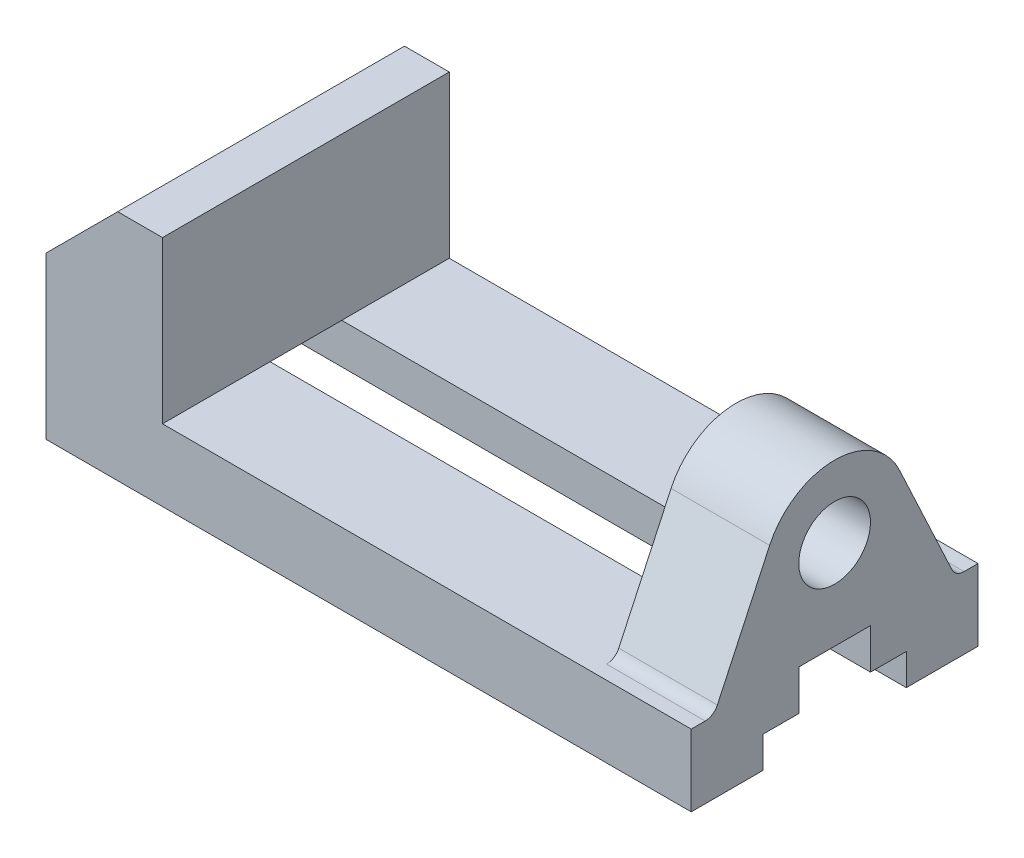
SolidWorks part; units mm, degrees
ref_plane "Front Plane" through (0, 0, 0) normal (0, 0, 1) x (1, 0, 0)
ref_plane "Top Plane" through (0, 0, 0) normal (0, 1, 0) x (1, 0, 0)
ref_plane "Right Plane" through (0, 0, 0) normal (1, 0, 0) x (0, 0, -1)
sketch "Sketch1" plane through (0, 0, 0) normal (0, 0, 1) x (1, 0, 0)
  line L1 (-72, 26) -> (72, 26)
  line L2 (-72, 26) -> (-72, -26)
  line L3 (-72, -26) -> (72, -26)
  line L4 (72, 26) -> (72, -26)
  line L5 (-72, 26) -> (72, -26) construction
  line L6 (-72, -26) -> (72, 26) construction
  point P0 (0, 0)
  dimension "D1" = 144
  dimension "D2" = 52
extrude "Boss-Extrude1" add sketch "Sketch1" along normal mid plane 64
sketch "Sketch2" plane through (0, 0, 32) normal (0, 0, 1) x (1, 0, 0)
  line L0 (-72, 26) -> (-72, -26) construction
  line L1 (-46, 40.9189) -> (50, 40.9189)
  line L2 (-46, 40.9189) -> (-46, -10)
  line L3 (-46, -10) -> (50, -10)
  line L4 (50, 40.9189) -> (50, -10)
  line L5 (72, 26) -> (-72, 26) construction
  line L6 (72, -26) -> (72, 26) construction
  dimension "D1" = 26
  dimension "D2" = 36
  dimension "D3" = 22
extrude "Cut-Extrude1" cut sketch "Sketch2" against normal blind 64
chamfer "Chamfer1" distance 16 distance2 16 1 edges at (-72, 26, 0)
sketch "Sketch3" plane through (72, 0, 0) normal (1, 0, 0) x (0, 0, -1)
  line L0 (-32, 26) -> (32, 26) construction
  line L1 (0, 10) -> (0, -29.5307) construction
  line L2 (28.8914, -10) -> (32, -10)
  line L3 (-28.8914, -10) -> (-32, -10)
  line L4 (-26.1725, -8.2679) -> (-14.5009, 16.7619)
  line L5 (14.5009, 16.7619) -> (26.1725, -8.2679)
  line L6 (-32, -26) -> (-32, 26) construction
  line L7 (32, -26) -> (32, 26) construction
  line L10 (-53.9891, 39.8961) -> (52.3683, 39.8961)
  line L11 (-53.9891, 39.8961) -> (-53.9891, -35.215)
  line L12 (-53.9891, -35.215) -> (52.3683, -35.215)
  line L13 (52.3683, 39.8961) -> (52.3683, -35.215)
  arc A0 (14.5009, 16.7619) -> (-14.5009, 16.7619) centre (0, 10) ccw
  circle A1 centre (0, 10) radius 8
  arc A2 (-26.1725, -8.2679) -> (-28.8914, -10) centre (-28.8914, -7) cw
  arc A3 (26.1725, -8.2679) -> (28.8914, -10) centre (28.8914, -7) ccw
  dimension "D1" = 32
  dimension "D3" = 16
  dimension "D2" = 3
  dimension "D6" = 3
  dimension "D4" = 25
  dimension "D5" = 25
extrude "Cut-Extrude7" cut sketch "Sketch3" against normal blind 22
sketch "Sketch6" plane through (72, 0, 0) normal (1, 0, 0) x (0, 0, -1)
  line L0 (8, -19) -> (16, -19)
  line L1 (-32, -26) -> (32, -26) construction
  line L2 (-16, -19) -> (-8, -19)
  line L3 (-16, -19) -> (-16, -26)
  line L4 (-16, -26) -> (16, -26)
  line L5 (16, -19) -> (16, -26)
  line L7 (-8, -10) -> (8, -10)
  line L8 (-8, -10) -> (-8, -19)
  line L10 (8, -10) -> (8, -19)
extrude "Cut-Extrude8" cut sketch "Sketch6" against normal through all
sketch "Sketch7" plane through (0, -26, 0) normal (0, -1, 0) x (-1, 0, 0)
  point P0 (36, -22)
  point P1 (-34, -22)
  point P2 (-34, 22)
  point P3 (36, 22)
hole_wizard "Ø6.0mm Dowel Hole1" positions "3DSketch2" profile "Sketch9" hole size "Ø6.0" standard "ISO"
sketch3d "3DSketch2"
  point P0 (-36, -26, 22)
  point P3 (34, -26, 22)
  point P6 (34, -26, -22)
  point P9 (-36, -26, -22)
sketch "Sketch9" plane through (-36, -26, 22) normal (1, 0, 0) x (0, 0, -1)
  line L0 (0, 0) -> (0, 11.8026)
  line L1 (0, 11.8026) -> (3, 10)
  line L2 (3, 10) -> (3, 0)
  line L5 (3, 0) -> (0, 0)
  line L10 (0, 11.8026) -> (-3, 10) construction
  line L11 (0, -6.35) -> (0, 107.95) construction
  dimension "Hole Dia." = 6
  dimension "Hole Depth" = 10
  dimension "Drill Angle" = 118
